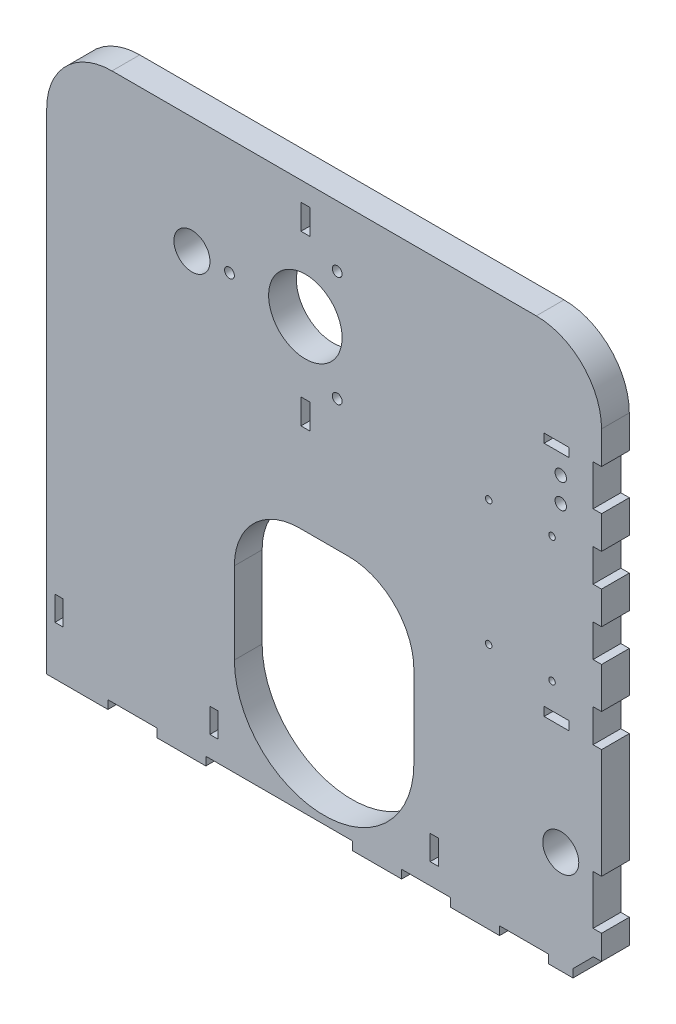
SolidWorks part; units mm, degrees
ref_plane "Front Plane" through (0, 0, 0) normal (0, 0, 1) x (1, 0, 0)
ref_plane "Top Plane" through (0, 0, 0) normal (0, 1, 0) x (1, 0, 0)
ref_plane "Right Plane" through (0, 0, 0) normal (1, 0, 0) x (0, 0, -1)
sketch "Model" plane through (0, 0, 0) normal (0, 0, 1) x (1, 0, 0)
  line L1248 (-49.1781, -373.4692) -> (-49.1781, -423.4692)
  line L1249 (60.8219, -423.4692) -> (60.8219, -373.4692)
  line L1250 (20.8219, -333.4692) -> (-9.1781, -333.4692)
  line L1251 (-2.9781, -160.1192) -> (-2.9781, -175.5192)
  line L1252 (-2.9781, -175.5192) -> (-8.3781, -175.5192)
  line L1253 (-8.3781, -175.5192) -> (-8.3781, -160.1192)
  line L1254 (-8.3781, -160.1192) -> (-2.9781, -160.1192)
  line L1255 (-2.9781, -263.4192) -> (-2.9781, -278.8192)
  line L1256 (-2.9781, -278.8192) -> (-8.3781, -278.8192)
  line L1257 (-8.3781, -278.8192) -> (-8.3781, -263.4192)
  line L1258 (-8.3781, -263.4192) -> (-2.9781, -263.4192)
  line L1259 (75.8219, -455.4692) -> (75.8219, -470.4692)
  line L1260 (75.8219, -470.4692) -> (70.8219, -470.4692)
  line L1261 (70.8219, -470.4692) -> (70.8219, -455.4692)
  line L1262 (70.8219, -455.4692) -> (75.8219, -455.4692)
  line L1263 (170.6219, -313.3192) -> (170.6219, -293.3192)
  line L1264 (170.6219, -293.3192) -> (175.8219, -293.3192)
  line L1265 (175.8219, -293.3192) -> (175.8219, -273.3192)
  line L1266 (175.8219, -273.3192) -> (170.6219, -273.3192)
  line L1267 (170.6219, -273.3192) -> (170.6219, -253.3192)
  line L1268 (170.6219, -253.3192) -> (175.8219, -253.3192)
  line L1269 (175.8219, -253.3192) -> (175.8219, -233.3192)
  line L1270 (175.8219, -233.3192) -> (170.6219, -233.3192)
  line L1271 (170.6219, -233.3192) -> (170.6219, -208.3192)
  line L1272 (170.6219, -208.3192) -> (175.8219, -208.3192)
  line L1273 (175.8219, -208.3192) -> (175.8219, -188.3192)
  line L1274 (135.8219, -148.3192) -> (-124.1781, -148.3192)
  line L1275 (-164.1781, -188.3192) -> (-164.1781, -488.4692)
  line L1276 (-164.1781, -488.4692) -> (-126.6781, -488.4692)
  line L1277 (-126.6781, -488.4692) -> (-126.6781, -483.2692)
  line L1278 (-126.6781, -483.2692) -> (-96.6781, -483.2692)
  line L1279 (-96.6781, -483.2692) -> (-96.6781, -488.4692)
  line L1280 (-96.6781, -488.4692) -> (-66.6781, -488.4692)
  line L1281 (-66.6781, -488.4692) -> (-66.6781, -483.2692)
  line L1282 (-66.6781, -483.2692) -> (23.3219, -483.2692)
  line L1283 (23.3219, -483.2692) -> (23.3219, -488.4692)
  line L1284 (23.3219, -488.4692) -> (53.3219, -488.4692)
  line L1285 (53.3219, -488.4692) -> (53.3219, -483.2692)
  line L1286 (53.3219, -483.2692) -> (83.3219, -483.2692)
  line L1287 (83.3219, -483.2692) -> (83.3219, -488.4692)
  line L1288 (83.3219, -488.4692) -> (113.3219, -488.4692)
  line L1289 (113.3219, -488.4692) -> (113.3219, -483.2692)
  line L1290 (113.3219, -483.2692) -> (143.3219, -483.2692)
  line L1291 (143.3219, -483.2692) -> (143.3219, -488.4692)
  line L1292 (143.3219, -488.4692) -> (158.3219, -488.4692)
  line L1293 (158.3219, -488.4692) -> (158.3219, -483.4692)
  line L1294 (158.3219, -483.4692) -> (170.8219, -470.9692)
  line L1295 (170.8219, -470.9692) -> (175.8219, -470.9692)
  line L1296 (175.8219, -470.9692) -> (175.8219, -455.9692)
  line L1297 (175.8219, -455.9692) -> (170.6219, -455.9692)
  line L1298 (170.6219, -455.9692) -> (170.6219, -425.7692)
  line L1299 (170.6219, -425.7692) -> (175.8219, -425.7692)
  line L1300 (175.8219, -425.7692) -> (175.8219, -358.5192)
  line L1301 (175.8219, -358.5192) -> (170.6219, -358.5192)
  line L1302 (170.6219, -358.5192) -> (170.6219, -338.3192)
  line L1303 (170.6219, -338.3192) -> (175.8219, -338.3192)
  line L1304 (175.8219, -338.3192) -> (175.8219, -313.3192)
  line L1305 (175.8219, -313.3192) -> (170.6219, -313.3192)
  line L1306 (140.6219, -213.5192) -> (140.6219, -208.1192)
  line L1307 (140.6219, -208.1192) -> (156.0219, -208.1192)
  line L1308 (156.0219, -208.1192) -> (156.0219, -213.5192)
  line L1309 (156.0219, -213.5192) -> (140.6219, -213.5192)
  line L1310 (140.6219, -358.5192) -> (140.6219, -353.1192)
  line L1311 (140.6219, -353.1192) -> (156.0219, -353.1192)
  line L1312 (156.0219, -353.1192) -> (156.0219, -358.5192)
  line L1313 (156.0219, -358.5192) -> (140.6219, -358.5192)
  line L1314 (-154.1781, -443.4692) -> (-154.1781, -458.4692)
  line L1315 (-154.1781, -458.4692) -> (-159.1781, -458.4692)
  line L1316 (-159.1781, -458.4692) -> (-159.1781, -443.4692)
  line L1317 (-159.1781, -443.4692) -> (-154.1781, -443.4692)
  line L1318 (-59.1781, -455.4692) -> (-59.1781, -470.4692)
  line L1319 (-59.1781, -470.4692) -> (-64.1781, -470.4692)
  line L1320 (-64.1781, -470.4692) -> (-64.1781, -455.4692)
  line L1321 (-64.1781, -455.4692) -> (-59.1781, -455.4692)
  arc A426 (-9.1781, -333.4692) -> (-49.1781, -373.4692) centre (-9.1781, -373.4692) ccw
  arc A427 (-49.1781, -423.4692) -> (60.8219, -423.4692) centre (5.8219, -423.4692) ccw
  arc A428 (60.8219, -373.4692) -> (20.8219, -333.4692) centre (20.8219, -373.4692) ccw
  circle A429 centre (-75.1781, -219.4692) radius 11.05
  circle A430 centre (150.8219, -425.4692) radius 11.05
  circle A431 centre (-5.6781, -219.4692) radius 22.5
  circle A432 centre (13.8219, -253.2442) radius 3
  circle A433 centre (13.8219, -185.6942) radius 3
  circle A434 centre (-52.1781, -219.4692) radius 3
  arc A435 (175.8219, -188.3192) -> (135.8219, -148.3192) centre (135.8219, -188.3192) ccw
  arc A436 (-124.1781, -148.3192) -> (-164.1781, -188.3192) centre (-124.1781, -188.3192) ccw
  circle A437 centre (150.8219, -240.4692) radius 3.5
  circle A438 centre (150.8219, -225.4692) radius 3.5
  circle A439 centre (106.6719, -337.2692) radius 2
  circle A440 centre (145.4719, -260.4692) radius 2
  circle A441 centre (145.4719, -337.2692) radius 2
  circle A442 centre (106.6719, -260.4692) radius 2
extrude "Boss-Extrude1" add sketch "Model" along normal blind 17
